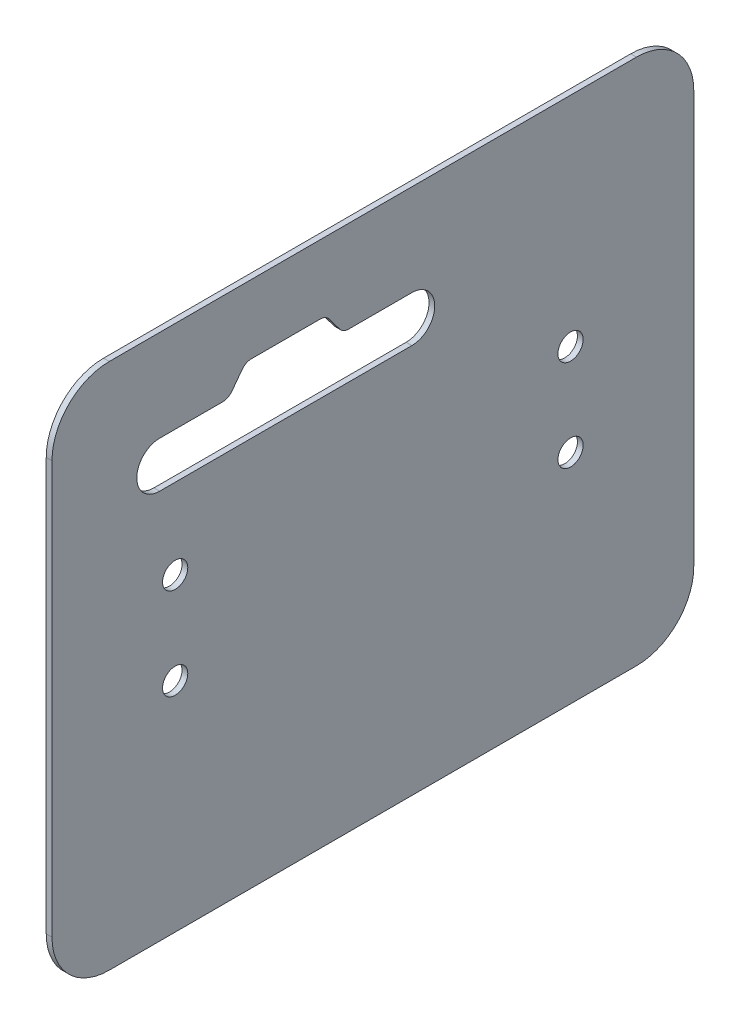
SolidWorks part; units mm, degrees
ref_plane "前视基准面" through (0, 0, 0) normal (0, 0, 1) x (1, 0, 0)
ref_plane "上视基准面" through (0, 0, 0) normal (0, 1, 0) x (1, 0, 0)
ref_plane "右视基准面" through (0, 0, 0) normal (1, 0, 0) x (0, 0, -1)
sketch "草图1" plane through (0, 0, 0) normal (1, 0, 0) x (0, 0, -1)
  line L0 (0, 26.064) -> (0, 0) construction
  line L1 (-23, 23) -> (23, 23)
  line L2 (-28, 18) -> (-28, -18)
  line L3 (-23, -23) -> (23, -23)
  line L4 (28, 18) -> (28, -18)
  line L5 (0, 0) -> (43.945, 0) construction
  arc A0 (-23, 23) -> (-28, 18) centre (-23, 18) ccw
  arc A1 (-28, -18) -> (-23, -23) centre (-23, -18) ccw
  arc A2 (23, -23) -> (28, -18) centre (23, -18) ccw
  arc A3 (23, 23) -> (28, 18) centre (23, 18) cw
  circle A4 centre (17.25, 4) radius 1.1 construction
  circle A5 centre (17.25, -4) radius 1.1 construction
  circle A6 centre (-17.25, -4) radius 1.1 construction
  circle A7 centre (-17.25, 4) radius 1.1 construction
  circle A8 centre (17.25, 4) radius 1.1
  circle A9 centre (17.25, -4) radius 1.1
  circle A10 centre (-17.25, -4) radius 1.1
  circle A11 centre (-17.25, 4) radius 1.1
  point P10 (-28, 23)
  point P13 (-28, -23)
  point P18 (28, 23)
  dimension "D3" = 5
  dimension "D1" = 56
  dimension "D2" = 46
extrude "凸台-拉伸1" add sketch "草图1" along normal blind 0.5
sketch "草图2" plane through (0.5, 0, 0) normal (1, 0, 0) x (0, 0, -1)
  line L0 (-18.6, 13) -> (3.4, 13) construction
  line L1 (-18.6, 15) -> (3.4, 15)
  line L2 (-18.6, 11) -> (3.4, 11)
  line L3 (-7.6, 8.65) -> (-7.6, 22.4487) construction
  line L4 (-3.1, 8.65) -> (-12.1, 8.65) construction
  line L5 (-2.6, 13) -> (-7.6, 13) construction
  line L7 (-11.1, 17) -> (-12.6, 15)
  line L8 (23, 23) -> (-23, 23) construction
  line L10 (-11.1, 17) -> (-4.1, 17)
  line L13 (-2.6, 15) -> (-4.1, 17)
  arc A0 (-18.6, 15) -> (-18.6, 11) centre (-18.6, 13) ccw
  arc A1 (3.4, 11) -> (3.4, 15) centre (3.4, 13) ccw
  point P2 (-7.6, 13)
  dimension "D1" = 2
  dimension "D2" = 22
  dimension "D3" = 2
  dimension "D4" = 7
  dimension "D5" = 10
  dimension "D6" = 10
extrude "切除-拉伸1" cut sketch "草图2" against normal blind 10 contours L2 A1 L1 A0 | L1 L13 L10 L7
fillet "圆角1" radius 1 4 edges at (0.25, 17, 11.1) (0.25, 15, 12.6) (0.25, 17, 4.1) (0.25, 15, 2.6)
sketch "草图3" plane through (0, 0, 0) normal (-1, 0, 0) x (0, 0, 1)
  line L0 (-13.6472, -19.5) -> (18, -19.5)
  line L1 (21, -16.5) -> (21, 13)
  line L2 (18, 16) -> (-2.5, 16)
  line L3 (-7.5, 14.6603) -> (-20.25, 7.299)
  line L4 (-21, 6) -> (-21, -6)
  line L5 (-14.9954, -18.6576) -> (-20.8482, -6.6576)
  arc A0 (-14.9954, -18.6576) -> (-13.6472, -19.5) centre (-13.6472, -18) ccw
  arc A1 (-20.8482, -6.6576) -> (-21, -6) centre (-19.5, -6) cw
  arc A2 (-20.25, 7.299) -> (-21, 6) centre (-19.5, 6) ccw
  arc A3 (21, 13) -> (18, 16) centre (18, 13) ccw
  arc A4 (18, -19.5) -> (21, -16.5) centre (18, -16.5) ccw
  arc A5 (-2.5, 16) -> (-7.5, 14.6603) centre (-2.5, 6) ccw
  arc A6 (-20.5, -6) -> (-19.5, -7) centre (-19.5, -6) ccw construction
  arc A7 (-19.5, 7) -> (-20.5, 6) centre (-19.5, 6) ccw construction
  dimension "D1" = 1.5
  dimension "D2" = 10
  dimension "D3" = 3
  dimension "D4" = 16
  dimension "D5" = 21
  dimension "D6" = 19.5
  dimension "D7" = 120
  dimension "D8" = 116
extrude "拉伸-薄壁1" [suppressed] add sketch "草图3" along normal up to surface (15 mm away) thin
